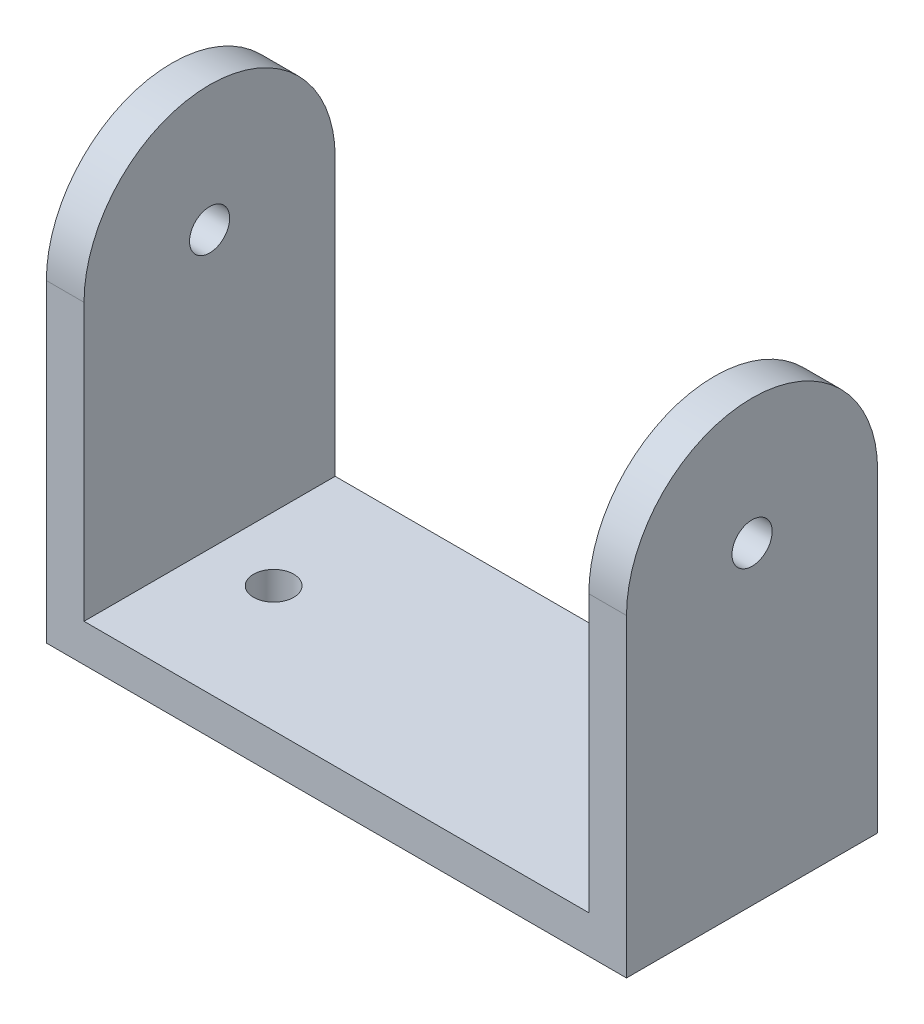
SolidWorks part; units mm, degrees
ref_plane "Plan de face" through (0, 0, 0) normal (0, 0, 1) x (1, 0, 0)
ref_plane "Plan de dessus" through (0, 0, 0) normal (0, 1, 0) x (1, 0, 0)
ref_plane "Plan de droite" through (0, 0, 0) normal (1, 0, 0) x (0, 0, -1)
sketch "Esquisse1" plane through (0, 0, 0) normal (0, 1, 0) x (1, 0, 0)
  line L1 (-20.1, 10) -> (20.1, 10)
  line L2 (-20.1, 10) -> (-20.1, -10)
  line L3 (-20.1, -10) -> (20.1, -10)
  line L4 (20.1, 10) -> (20.1, -10)
  line L5 (-20.1, 10) -> (20.1, -10) construction
  line L6 (-20.1, -10) -> (20.1, 10) construction
  point P0 (0, 0)
  dimension "D1" = 40.2
  dimension "D2" = 20
extrude "Boss.-Extru.1" add sketch "Esquisse1" along normal blind 3
sketch "Esquisse2" plane through (0, 0, 0) normal (0, -1, 0) x (1, 0, 0)
  line L0 (20.1, -10) -> (-20.1, -10) construction
  line L1 (-20.1, 10) -> (-23.1, 10)
  line L2 (-20.1, 10) -> (-20.1, -10)
  line L3 (-20.1, -10) -> (-23.1, -10)
  line L4 (-23.1, 10) -> (-23.1, -10)
  line L5 (20.1, 10) -> (23.1, 10)
  line L6 (20.1, 10) -> (20.1, -10)
  line L7 (20.1, -10) -> (23.1, -10)
  line L8 (23.1, 10) -> (23.1, -10)
  dimension "D1" = 3
  dimension "D2" = 3
extrude "Boss.-Extru.2" add sketch "Esquisse2" against normal blind 35
sketch "Esquisse3" plane through (23.1, 0, 0) normal (1, 0, 0) x (0, 0, -1)
  line L0 (0, 35) -> (0, 25) construction
  line L1 (10, 35) -> (-10, 35) construction
  line L2 (10, 35) -> (10, 0) construction
  line L3 (-10, 35) -> (-10, 0) construction
  line L4 (-10, 25) -> (-10, 35)
  line L5 (-10, 35) -> (10, 35)
  line L6 (10, 35) -> (10, 25)
  arc A0 (10, 25) -> (-10, 25) centre (0, 25) ccw
  line M3 (10, 0) -> (10, 35)
  line M4 (10, 35) -> (-10, 35)
  line M5 (-10, 35) -> (-10, 0)
  dimension "D1" = 10
extrude "Enlèv. mat.-Extru.1" cut sketch "Esquisse3" against normal blind 71 contours A0 L5 M5 | A0 M3 M4
sketch "Esquisse4" plane through (23.1, 0, 0) normal (1, 0, 0) x (0, 0, -1)
  line L0 (0, 35) -> (0, 25) construction
  arc A0 (10, 25) -> (-10, 25) centre (0, 25) ccw construction
  circle A1 centre (0, 25) radius 1.6
  dimension "D1" = 3.2
extrude "Enlèv. mat.-Extru.2" cut sketch "Esquisse4" against normal blind 71
sketch "Esquisse5" plane through (0, 3, 0) normal (0, 1, 0) x (1, 0, 0)
  line L0 (-20.1, 0) -> (20.1, 0) construction
  line L1 (-20.1, -10) -> (-20.1, 10) construction
  line L2 (20.1, -10) -> (20.1, 10) construction
  circle A0 centre (-15, 0) radius 1.6
  circle A1 centre (15, 0) radius 1.6
  dimension "D1" = 3.2
  dimension "D2" = 15
  dimension "D3" = 15
extrude "Enlèv. mat.-Extru.3" cut sketch "Esquisse5" against normal blind 71
